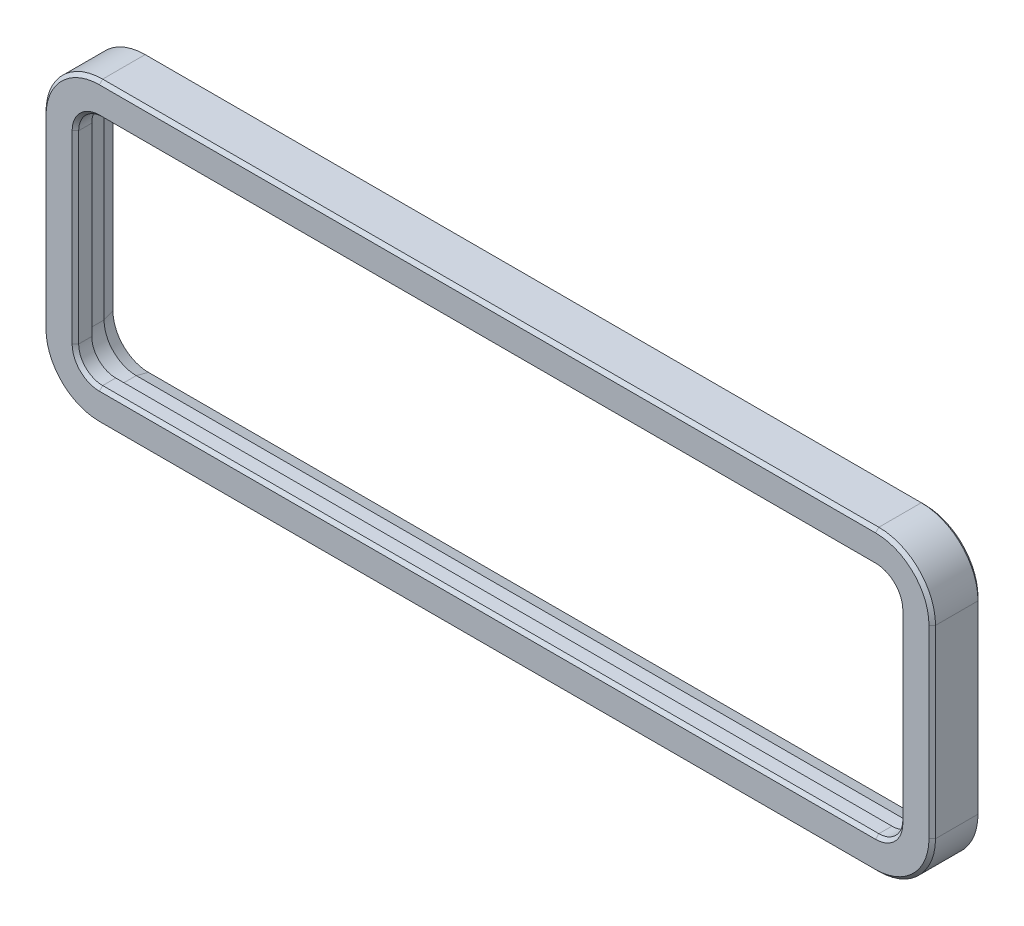
SolidWorks part; units mm, degrees
ref_plane "Front Plane" through (0, 0, 0) normal (0, 0, 1) x (1, 0, 0)
ref_plane "Top Plane" through (0, 0, 0) normal (0, 1, 0) x (1, 0, 0)
ref_plane "Right Plane" through (0, 0, 0) normal (1, 0, 0) x (0, 0, -1)
sketch "Sketch1" plane through (0, 0, 0) normal (0, 0, 1) x (1, 0, 0)
  line L1 (0, 0) -> (102.87, 0)
  line L2 (0, 0) -> (0, 30.48)
  line L3 (0, 30.48) -> (102.87, 30.48)
  line L4 (102.87, 0) -> (102.87, 30.48)
  dimension "D1" = 102.87
  dimension "D2" = 30.48
extrude "Boss-Extrude1" add sketch "Sketch1" along normal blind 1.57
fillet "Fillet1" radius 3.935 4 edges at (0, 0, 0.785) (102.87, 0, 0.785) (102.87, 30.48, 0.785) (0, 30.48, 0.785)
hole_wizard "CSK for #6 Flat Head Machine Screw1" [suppressed] positions "Sketch3" profile "Sketch4" countersink size "#6" standard "ANSI Inch"
sketch "Sketch3" plane through (0, 0, 1.57) normal (0, 0, 1) x (1, 0, 0)
  line L0 (0, 26.545) -> (0, 3.935) construction
  line L1 (98.935, 30.48) -> (3.935, 30.48) construction
  line L2 (3.935, 0) -> (98.935, 0) construction
  line L3 (102.87, 3.935) -> (102.87, 26.545) construction
  point P0 (3.937, 26.4795)
  point P8 (3.937, 4.0005)
  point P10 (98.933, 26.4795)
  point P12 (98.933, 4.0005)
  dimension "D1" = 3.937
  dimension "D2" = 4.0005
  dimension "D3" = 3.937
  dimension "D4" = 4.0005
  dimension "D5" = 3.937
  dimension "D6" = 4.0005
  dimension "D7" = 4.0005
  dimension "D8" = 3.937
sketch "Sketch4" plane through (3.937, 26.4795, 1.57) normal (1, 0, 0) x (0, -1, 0)
  line L0 (0, 0) -> (0, 1.57)
  line L1 (0, 1.57) -> (2.0955, 1.57)
  line L2 (2.0955, 1.57) -> (2.0955, 0.9496)
  line L3 (2.0955, 0.9496) -> (2.921, 0)
  line L5 (2.921, 0) -> (0, 0)
  line L6 (-2.0955, 0.9496) -> (-2.921, 0) construction
  line L11 (0, -6.35) -> (0, 107.95) construction
  dimension "Thru Hole Dia." = 4.191
  dimension "Thru Hole Depth" = 1.57
  dimension "Near C'Sink Dia." = 5.842
  dimension "Near C'Sink Angle" = 82
sketch "data side" [suppressed] plane through (0, 0, 0) normal (0, 0, 1) x (1, 0, 0)
  line L0 (1.435, 10.7795) -> (0, 10.7795) construction
  line L1 (1.435, 10.7795) -> (101.435, 10.7795) construction
  line L2 (1.435, 10.7795) -> (1.435, 12.3495) construction
  line L3 (1.435, 12.3495) -> (101.435, 12.3495) construction
  line L4 (101.435, 10.7795) -> (101.435, 12.3495) construction
  line L6 (101.435, 10.7795) -> (102.87, 10.7795) construction
  line L8 (102.87, 3.935) -> (102.87, 26.545) construction
  line L21 (0, 26.545) -> (0, 3.935) construction
  line L22 (3.935, 0) -> (98.935, 0) construction
  line L23 (46.965, 14.0295) -> (55.905, 14.0295) construction
  line L24 (48.265, 15.7095) -> (54.605, 15.7095)
  line L25 (46.965, 14.4095) -> (46.965, 13.6495)
  line L26 (48.265, 12.3495) -> (54.605, 12.3495)
  line L27 (55.905, 14.4095) -> (55.905, 13.6495)
  line L28 (51.435, 12.3495) -> (51.435, 15.7095) construction
  line L29 (46.965, 15.7095) -> (0, 15.7095) construction
  line L30 (55.905, 15.7095) -> (102.87, 15.7095) construction
  arc A1 (54.605, 12.3495) -> (55.905, 13.6495) centre (54.605, 13.6495) ccw
  arc A2 (54.605, 15.7095) -> (55.905, 14.4095) centre (54.605, 14.4095) cw
  arc A3 (46.965, 13.6495) -> (48.265, 12.3495) centre (48.265, 13.6495) ccw
  arc A4 (48.265, 15.7095) -> (46.965, 14.4095) centre (48.265, 14.4095) ccw
  circle A5 centre (16.435, 18.8995) radius 3.25
  circle A6 centre (87.435, 14.8495) radius 2.5
  point P32 (46.965, 12.3495)
  dimension "D4" = 5
  dimension "D5" = 2.5
  dimension "D6" = 6.5
  dimension "D10" = 1.3
  dimension "D13" = 14
  dimension "D2" = 1.57
  dimension "D3" = 100
  dimension "D7" = 8.94
  dimension "D8" = 3.36
  dimension "D11" = 6.55
  dimension "D12" = 15
  dimension "D14" = 10.7795
sketch "io side" [suppressed] plane through (0, 0, 1.57) normal (0, 0, 1) x (1, 0, 0)
  line L0 (1.435, 10.7795) -> (0, 10.7795) construction
  line L1 (1.435, 10.7795) -> (101.435, 10.7795) construction
  line L2 (1.435, 10.7795) -> (1.435, 12.3495) construction
  line L3 (1.435, 12.3495) -> (101.435, 12.3495) construction
  line L4 (101.435, 10.7795) -> (101.435, 12.3495) construction
  line L5 (0, 26.545) -> (0, 3.935) construction
  line L6 (101.435, 10.7795) -> (102.87, 10.7795) construction
  line L7 (102.87, 3.935) -> (102.87, 26.545) construction
  line L9 (75.385, 19.8995) -> (83.785, 19.8995)
  line L10 (75.385, 19.8995) -> (75.385, 12.3495)
  line L11 (75.385, 12.3495) -> (83.785, 12.3495)
  line L12 (83.785, 19.8995) -> (83.785, 12.3495)
  line L13 (43.79, 19.8995) -> (59.19, 19.8995)
  line L14 (43.79, 19.8995) -> (43.79, 12.3495)
  line L15 (43.79, 12.3495) -> (59.19, 12.3495)
  line L16 (59.19, 19.8995) -> (59.19, 12.3495)
  line L17 (9.985, 12.3495) -> (28.885, 12.3495)
  line L18 (9.985, 12.3495) -> (9.985, 19.8995)
  line L19 (9.985, 19.8995) -> (28.885, 19.8995)
  line L20 (28.885, 12.3495) -> (28.885, 19.8995)
  circle A0 centre (89.8563, 16.7478) radius 2.15
  dimension "D4" = 4.3983
  dimension "D5" = 11.5787
  dimension "D6" = 4.3
  dimension "D1" = 10.7795
  dimension "D2" = 1.57
  dimension "D3" = 100
  dimension "D7" = 8.4
  dimension "D8" = 7.55
  dimension "D9" = 17.65
  dimension "D10" = 15.4
  dimension "D11" = 18.9
  dimension "D12" = 42.245
  dimension "D13" = 72.55
sketch "Sketch6" [suppressed] plane through (0, 0, 1.57) normal (0, 0, 1) x (1, 0, 0)
  line L0 (75.385, 19.8995) -> (75.385, 12.3495) construction
  line L1 (75.385, 12.3495) -> (83.785, 12.3495) construction
  line L2 (83.785, 19.8995) -> (83.785, 12.3495) construction
  line L3 (75.385, 19.8995) -> (83.785, 19.8995) construction
  line L4 (59.19, 19.8995) -> (59.19, 12.3495) construction
  line L5 (43.79, 12.3495) -> (59.19, 12.3495) construction
  line L6 (43.79, 19.8995) -> (43.79, 12.3495) construction
  line L7 (43.79, 19.8995) -> (59.19, 19.8995) construction
  line L8 (9.985, 12.3495) -> (9.985, 19.8995) construction
  line L9 (9.985, 12.3495) -> (28.885, 12.3495) construction
  line L10 (28.885, 12.3495) -> (28.885, 19.8995) construction
  line L11 (9.985, 19.8995) -> (28.885, 19.8995) construction
  line L12 (75.385, 19.8995) -> (75.385, 12.3495)
  line L13 (75.385, 12.3495) -> (83.785, 12.3495)
  line L14 (83.785, 19.8995) -> (83.785, 12.3495)
  line L15 (75.385, 19.8995) -> (83.785, 19.8995)
  line L16 (59.19, 19.8995) -> (59.19, 12.3495)
  line L17 (43.79, 12.3495) -> (59.19, 12.3495)
  line L18 (43.79, 19.8995) -> (43.79, 12.3495)
  line L19 (43.79, 19.8995) -> (59.19, 19.8995)
  line L20 (9.985, 12.3495) -> (9.985, 19.8995)
  line L21 (9.985, 12.3495) -> (28.885, 12.3495)
  line L22 (28.885, 12.3495) -> (28.885, 19.8995)
  line L23 (9.985, 19.8995) -> (28.885, 19.8995)
  circle A0 centre (89.8563, 16.7478) radius 2.15 construction
  circle A1 centre (89.8563, 16.7478) radius 2.15
extrude "Cut-Extrude1" [suppressed] cut sketch "Sketch6" against normal through all
other "Move Face1" [suppressed] parameters "D1"=0.4
extrude "Cut-Extrude9" [suppressed] cut sketch "data side" along normal up to surface (1.57 mm away)
other "Move Face4" [suppressed] parameters "D1"=0.5
sketch "Sketch7" plane through (0, 0, 1.57) normal (0, 0, 1) x (1, 0, 0)
  line L8 (-3, 26.545) -> (-3, 3.935)
  line L9 (3.935, -3) -> (98.935, -3)
  line L10 (105.87, 3.935) -> (105.87, 26.545)
  line L11 (98.935, 33.48) -> (3.935, 33.48)
  line L12 (-3, 26.545) -> (-3, 3.935)
  line L13 (3.935, -3) -> (98.935, -3)
  line L14 (105.87, 3.935) -> (105.87, 26.545)
  line L15 (98.935, 33.48) -> (3.935, 33.48)
  line L32 (0, 26.545) -> (0, 3.935) construction
  line L33 (3.935, 0) -> (98.935, 0) construction
  line L34 (102.87, 3.935) -> (102.87, 26.545) construction
  line L35 (98.935, 30.48) -> (3.935, 30.48) construction
  line L36 (0, 26.545) -> (0, 3.935)
  line L37 (3.935, 0) -> (98.935, 0)
  line L38 (102.87, 3.935) -> (102.87, 26.545)
  line L39 (98.935, 30.48) -> (3.935, 30.48)
  arc A8 (-3, 3.935) -> (3.935, -3) centre (3.935, 3.935) ccw
  arc A9 (98.935, -3) -> (105.87, 3.935) centre (98.935, 3.935) ccw
  arc A10 (105.87, 26.545) -> (98.935, 33.48) centre (98.935, 26.545) ccw
  arc A11 (3.935, 33.48) -> (-3, 26.545) centre (3.935, 26.545) ccw
  arc A12 (-3, 3.935) -> (3.935, -3) centre (3.935, 3.935) ccw
  arc A13 (98.935, -3) -> (105.87, 3.935) centre (98.935, 3.935) ccw
  arc A14 (105.87, 26.545) -> (98.935, 33.48) centre (98.935, 26.545) ccw
  arc A15 (3.935, 33.48) -> (-3, 26.545) centre (3.935, 26.545) ccw
  arc A28 (0, 3.935) -> (3.935, 0) centre (3.935, 3.935) ccw construction
  arc A29 (98.935, 0) -> (102.87, 3.935) centre (98.935, 3.935) ccw construction
  arc A30 (102.87, 26.545) -> (98.935, 30.48) centre (98.935, 26.545) ccw construction
  arc A31 (3.935, 30.48) -> (0, 26.545) centre (3.935, 26.545) ccw construction
  arc A32 (0, 3.935) -> (3.935, 0) centre (3.935, 3.935) ccw
  arc A33 (98.935, 0) -> (102.87, 3.935) centre (98.935, 3.935) ccw
  arc A34 (102.87, 26.545) -> (98.935, 30.48) centre (98.935, 26.545) ccw
  arc A35 (3.935, 30.48) -> (0, 26.545) centre (3.935, 26.545) ccw
  dimension "D1" = 3
extrude "Boss-Extrude2" add sketch "Sketch7" along normal blind 2 separate body
sketch "Sketch9" plane through (0, 0, 1.57) normal (0, 0, -1) x (-1, 0, 0)
  line L4 (-3.935, 33.48) -> (-98.935, 33.48)
  line L5 (-105.87, 26.545) -> (-105.87, 3.935)
  line L6 (-98.935, -3) -> (-3.935, -3)
  line L7 (3, 3.935) -> (3, 26.545)
  line L8 (-3.935, 33.48) -> (-98.935, 33.48)
  line L9 (-105.87, 26.545) -> (-105.87, 3.935)
  line L10 (-98.935, -3) -> (-3.935, -3)
  line L11 (3, 3.935) -> (3, 26.545)
  line L12 (-98.935, 0) -> (-3.935, 0)
  line L13 (0, 3.935) -> (0, 26.545)
  line L14 (-3.935, 30.48) -> (-98.935, 30.48)
  line L15 (-102.87, 26.545) -> (-102.87, 3.935)
  line L16 (-98.935, 0) -> (-3.935, 0)
  line L17 (0, 3.935) -> (0, 26.545)
  line L18 (-3.935, 30.48) -> (-98.935, 30.48)
  line L19 (-102.87, 26.545) -> (-102.87, 3.935)
  arc A4 (3, 26.545) -> (-3.935, 33.48) centre (-3.935, 26.545) ccw
  arc A5 (-98.935, 33.48) -> (-105.87, 26.545) centre (-98.935, 26.545) ccw
  arc A6 (-105.87, 3.935) -> (-98.935, -3) centre (-98.935, 3.935) ccw
  arc A7 (-3.935, -3) -> (3, 3.935) centre (-3.935, 3.935) ccw
  arc A8 (3, 26.545) -> (-3.935, 33.48) centre (-3.935, 26.545) ccw
  arc A9 (-98.935, 33.48) -> (-105.87, 26.545) centre (-98.935, 26.545) ccw
  arc A10 (-105.87, 3.935) -> (-98.935, -3) centre (-98.935, 3.935) ccw
  arc A11 (-3.935, -3) -> (3, 3.935) centre (-3.935, 3.935) ccw
  arc A12 (-3.935, 0) -> (0, 3.935) centre (-3.935, 3.935) ccw
  arc A13 (0, 26.545) -> (-3.935, 30.48) centre (-3.935, 26.545) ccw
  arc A14 (-98.935, 30.48) -> (-102.87, 26.545) centre (-98.935, 26.545) ccw
  arc A15 (-102.87, 3.935) -> (-98.935, 0) centre (-98.935, 3.935) ccw
  arc A16 (-3.935, 0) -> (0, 3.935) centre (-3.935, 3.935) ccw
  arc A17 (0, 26.545) -> (-3.935, 30.48) centre (-3.935, 26.545) ccw
  arc A18 (-98.935, 30.48) -> (-102.87, 26.545) centre (-98.935, 26.545) ccw
  arc A19 (-102.87, 3.935) -> (-98.935, 0) centre (-98.935, 3.935) ccw
  dimension "D1" = 0
  dimension "D2" = 0
extrude "Boss-Extrude4" add sketch "Sketch9" along normal blind 4
sketch "Sketch11" plane through (0, 0, 3.57) normal (0, 0, 1) x (1, 0, 0)
  line L23 (101.87, 3.935) -> (101.87, 26.545)
  line L24 (3.935, 1) -> (98.935, 1)
  line L25 (1, 26.545) -> (1, 3.935)
  line L26 (98.935, 29.48) -> (3.935, 29.48)
  line L27 (101.87, 3.935) -> (101.87, 26.545)
  line L28 (3.935, 1) -> (98.935, 1)
  line L29 (1, 26.545) -> (1, 3.935)
  line L30 (98.935, 29.48) -> (3.935, 29.48)
  line L31 (-3, 26.545) -> (-3, 3.935)
  line L32 (3.935, -3) -> (98.935, -3)
  line L33 (105.87, 3.935) -> (105.87, 26.545)
  line L34 (98.935, 33.48) -> (3.935, 33.48)
  line L35 (-3, 26.545) -> (-3, 3.935)
  line L36 (3.935, -3) -> (98.935, -3)
  line L37 (105.87, 3.935) -> (105.87, 26.545)
  line L38 (98.935, 33.48) -> (3.935, 33.48)
  arc A21 (98.935, 1) -> (101.87, 3.935) centre (98.935, 3.935) ccw
  arc A22 (101.87, 26.545) -> (98.935, 29.48) centre (98.935, 26.545) ccw
  arc A23 (1, 3.935) -> (3.935, 1) centre (3.935, 3.935) ccw
  arc A24 (3.935, 29.48) -> (1, 26.545) centre (3.935, 26.545) ccw
  arc A25 (98.935, 1) -> (101.87, 3.935) centre (98.935, 3.935) ccw
  arc A26 (101.87, 26.545) -> (98.935, 29.48) centre (98.935, 26.545) ccw
  arc A27 (1, 3.935) -> (3.935, 1) centre (3.935, 3.935) ccw
  arc A28 (3.935, 29.48) -> (1, 26.545) centre (3.935, 26.545) ccw
  arc A29 (3.935, 33.48) -> (-3, 26.545) centre (3.935, 26.545) ccw
  arc A30 (-3, 3.935) -> (3.935, -3) centre (3.935, 3.935) ccw
  arc A31 (98.935, -3) -> (105.87, 3.935) centre (98.935, 3.935) ccw
  arc A32 (105.87, 26.545) -> (98.935, 33.48) centre (98.935, 26.545) ccw
  arc A33 (3.935, 33.48) -> (-3, 26.545) centre (3.935, 26.545) ccw
  arc A34 (-3, 3.935) -> (3.935, -3) centre (3.935, 3.935) ccw
  arc A35 (98.935, -3) -> (105.87, 3.935) centre (98.935, 3.935) ccw
  arc A36 (105.87, 26.545) -> (98.935, 33.48) centre (98.935, 26.545) ccw
  dimension "D1" = 1
  dimension "D2" = 0
extrude "Boss-Extrude5" add sketch "Sketch11" against normal up to surface (2 mm away) up to face at (51.435, 15.24, 1.57)
chamfer "Chamfer1" distance 0.4 angle 75 8 edges at (1.1525, 29.3275, -2.43) (0, 15.24, -2.43) (1.1525, 1.1525, -2.43) (51.435, 0, -2.43) (101.7175, 1.1525, -2.43) (102.87, 15.24, -2.43) (101.7175, 29.3275, -2.43) (51.435, 30.48, -2.43)
chamfer "Chamfer2" distance 0.4 angle 45 24 edges at (51.435, 33.48, -2.43) (103.8388, 31.4488, -2.43) (-0.9688, 31.4488, -2.43) (105.87, 15.24, -2.43) (-3, 15.24, -2.43) (103.8388, -0.9688, -2.43) (-0.9688, -0.9688, -2.43) (51.435, -3, -2.43) (101.87, 15.24, 3.57) (101.0104, 28.6204, 3.57) (51.435, 29.48, 3.57) (1.8596, 28.6204, 3.57) (1, 15.24, 3.57) (1.8596, 1.8596, 3.57) (51.435, 1, 3.57) (101.0104, 1.8596, 3.57) (51.435, 33.48, 3.57) (103.8388, 31.4488, 3.57) (105.87, 15.24, 3.57) (103.8388, -0.9688, 3.57) (51.435, -3, 3.57) (-0.9688, -0.9688, 3.57) (-3, 15.24, 3.57) (-0.9688, 31.4488, 3.57)
delete or keep bodies "Body-Delete/Keep 1" type keep bodies bodies 112
equation "\"D3@Sketch3\"=\"D1@Sketch3\""
equation "\"D4@Sketch3\"=\"D2@Sketch3\""
equation "\"D5@Sketch3\"=\"D1@Sketch3\""
equation "\"D6@Sketch3\"=\"D2@Sketch3\""
equation "\"D7@Sketch3\"=\"D2@Sketch3\""
equation "\"D8@Sketch3\"=\"D1@Sketch3\""
